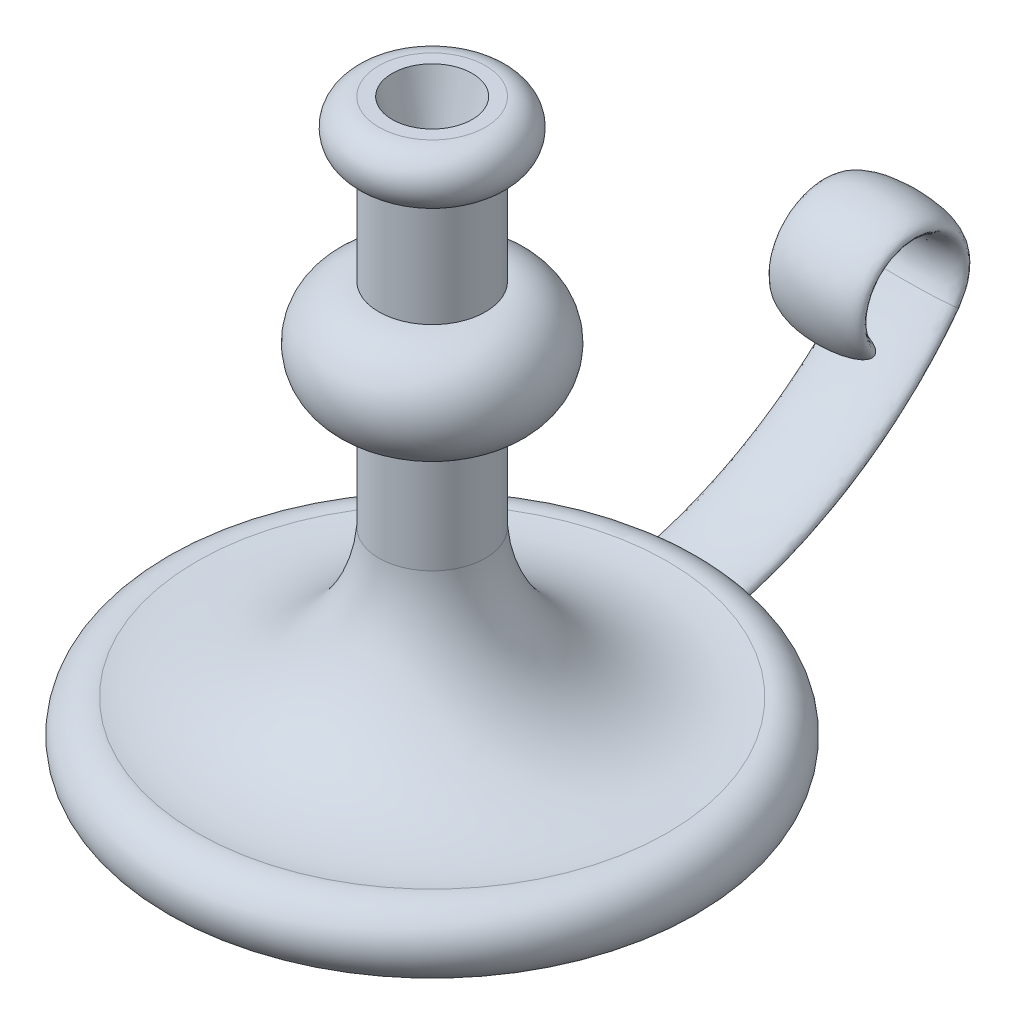
SolidWorks part; units mm, degrees
ref_plane "Płaszczyzna przednia" through (0, 0, 0) normal (0, 0, 1) x (1, 0, 0)
ref_plane "Płaszczyzna górna" through (0, 0, 0) normal (0, 1, 0) x (1, 0, 0)
ref_plane "Płaszczyzna prawa" through (0, 0, 0) normal (1, 0, 0) x (0, 0, -1)
sketch "Szkic1" plane through (0, 0, 0) normal (0, 0, 1) x (1, 0, 0)
  line L0 (0, 220) -> (0, 0)
  line L1 (0, 0) -> (90, 0)
  line L2 (0, 220) -> (20, 220)
  line L3 (20, 200) -> (20, 160)
  line L4 (20, 120) -> (20, 80)
  arc A0 (90, 0) -> (88.2494, 24.8768) centre (90, 12.5) ccw
  arc A1 (20, 220) -> (20, 200) centre (20, 210) cw
  arc A2 (20, 160) -> (20, 120) centre (20, 140) cw
  arc A4 (88.2494, 24.8768) -> (20, 80) centre (79.8468, 84.2855) cw
  dimension "D3" = 10
  dimension "D5" = 20
  dimension "D7" = 12.5
  dimension "D8" = 60
  dimension "D9" = 90
  dimension "D1" = 220
  dimension "D2" = 20
  dimension "D4" = 40
  dimension "D6" = 80
revolve "Obrót1" add sketch "Szkic1" angle 360 about L0
sketch "Szkic2" plane through (0, 0, 0) normal (1, 0, 0) x (0, 0, -1)
  line L0 (0, 0) -> (0, 10) construction
  line L2 (0, 10) -> (60, 10)
  line L3 (-90, 0) -> (90, 0) construction
  arc A0 (60, 10) -> (180, 70) centre (60, 160) ccw
  arc A1 (180, 70) -> (148, 70) centre (164, 82) ccw
  dimension "D3" = 150
  dimension "D5" = 20
  dimension "D1" = 60
  dimension "D2" = 10
  dimension "D4" = 60
sketch "Szkic3" plane through (0, 0, 0) normal (0, 0, 1) x (1, 0, 0)
  line L0 (0, 220) -> (0, 195)
  line L3 (0, 220) -> (0, 0) construction
  line L4 (0, 220) -> (15, 220)
  line L5 (0, 220) -> (20, 220) construction
  line L6 (15, 220) -> (8.3013, 195)
  line L7 (0, 195) -> (8.3013, 195)
  dimension "D1" = 25
  dimension "D2" = 15
  dimension "D3" = 15
revolve "Wycięcie-obrót1" cut sketch "Szkic3" angle 360 about L0
sketch "Szkic6" plane through (0, 0, 0) normal (0, 0, 1) x (1, 0, 0)
  line L0 (0, 220) -> (0, 0) construction
  ellipse E0 centre (0, 10.5133) end of major axis (17.5, 10.5133) minor radius 5
  dimension "D1" = 35
  dimension "D2" = 10
sweep "Wyciągnięcie po ścieżce1" add profiles "Szkic6" path "Szkic2"
